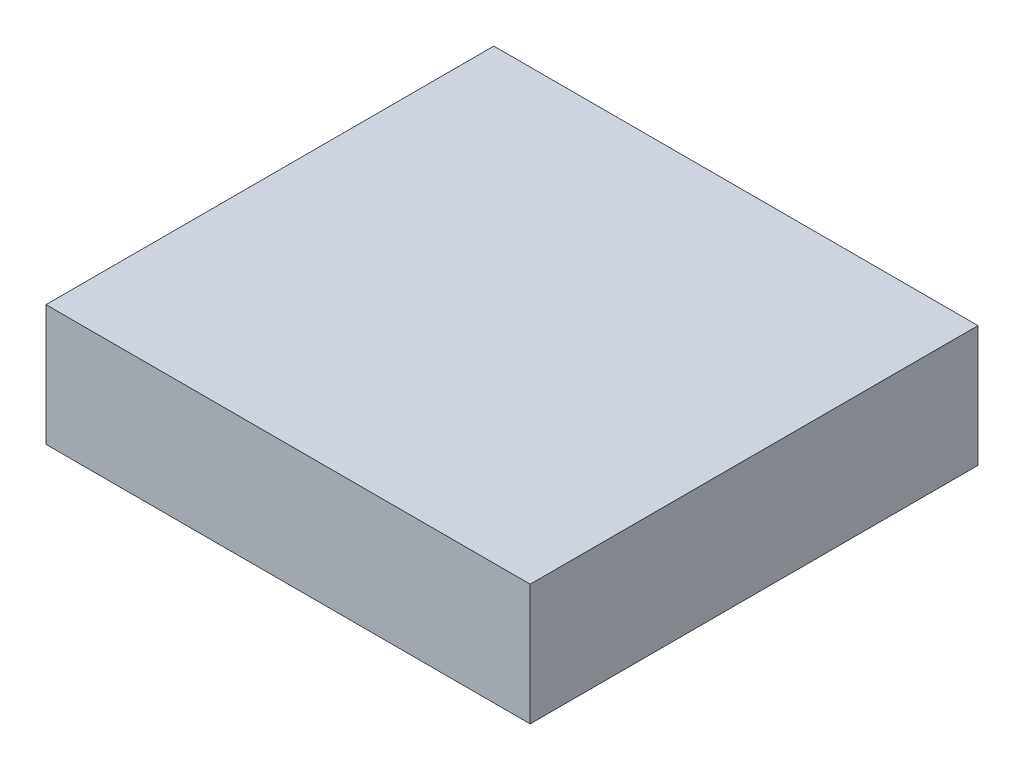
SolidWorks part; units mm, degrees
ref_plane "Front Plane" through (0, 0, 0) normal (0, 0, 1) x (1, 0, 0)
ref_plane "Top Plane" through (0, 0, 0) normal (0, 1, 0) x (1, 0, 0)
ref_plane "Right Plane" through (0, 0, 0) normal (1, 0, 0) x (0, 0, -1)
sketch "Sketch1" plane through (0, 0, 0) normal (0, 1, 0) x (1, 0, 0)
  line L1 (0, 0) -> (40, 0)
  line L2 (0, 0) -> (0, 37)
  line L3 (0, 37) -> (40, 37)
  line L4 (40, 0) -> (40, 37)
extrude "Boss-Extrude1" add sketch "Sketch1" along normal blind 10
